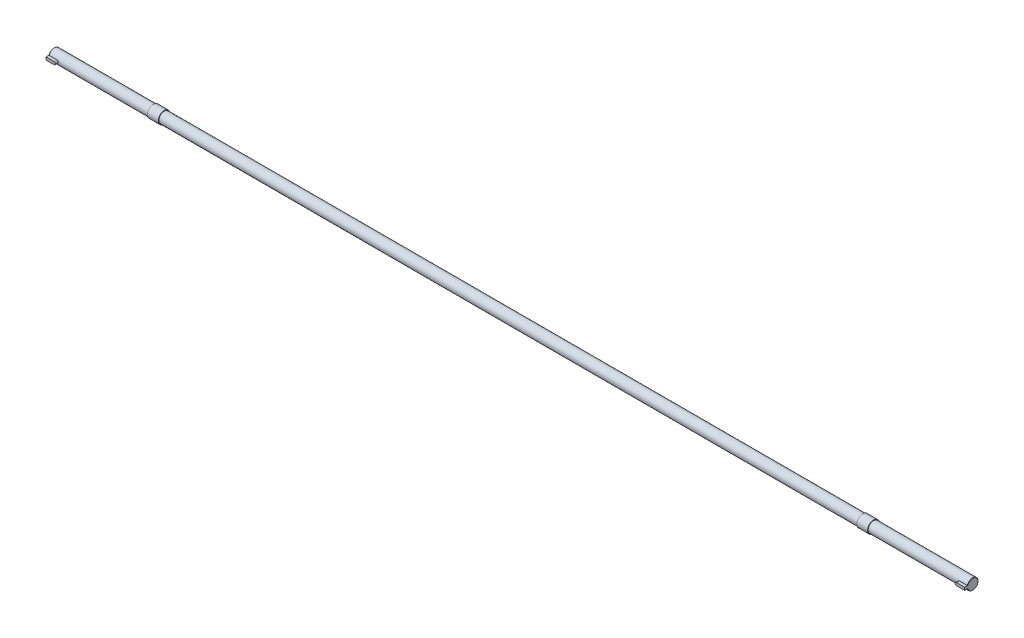
SolidWorks part; units mm, degrees
ref_plane "Front Plane" through (0, 0, 0) normal (0, 0, 1) x (1, 0, 0)
ref_plane "Top Plane" through (0, 0, 0) normal (0, 1, 0) x (1, 0, 0)
ref_plane "Right Plane" through (0, 0, 0) normal (1, 0, 0) x (0, 0, -1)
sketch "Sketch1" plane through (0, 0, 0) normal (0, 0, 1) x (1, 0, 0)
  line L0 (-1695, 0) -> (1695, 0)
  line L1 (1695, 0) -> (1695, -20)
  line L2 (1695, -20) -> (1328.75, -20)
  line L3 (1328.75, -20) -> (1328.75, -22)
  line L4 (1328.75, -22) -> (1288.75, -22)
  line L5 (1288.75, -22) -> (1288.75, -20)
  line L6 (1288.75, -20) -> (-1288.75, -20)
  line L7 (-1288.75, -20) -> (-1288.75, -22)
  line L8 (-1288.75, -22) -> (-1328.75, -22)
  line L9 (-1328.75, -22) -> (-1328.75, -20)
  line L10 (-1328.75, -20) -> (-1695, -20)
  line L11 (-1695, -20) -> (-1695, 0)
  point P3 (1308.75, -22)
  point P14 (-1308.75, -22)
  dimension "D3" = 20
  dimension "D4" = 22
  dimension "D5" = 22
  dimension "D6" = 40
  dimension "D7" = 40
  dimension "D8" = 3390
  dimension "D9" = 1695
  dimension "D10" = 386.25
  dimension "D11" = 386.25
revolve "Revolve1" add sketch "Sketch1" angle 360 about L0
chamfer "Chamfer1" distance 1 angle 45 2 edges at (-1695, -20, 0) (1695, -20, 0)
ref_plane "Plane1" through (0, 0, 20) normal (0, 0, 1) x (1, 0, 0)
sketch "Sketch3" plane through (0, 0, 20) normal (0, 0, 1) x (1, 0, 0)
  line L1 (1665, 5) -> (1695, 5)
  line L3 (1665, -5) -> (1695, -5)
  line L4 (1695, 5) -> (1695, -5)
  line L5 (1694, 20) -> (1328.75, 20) construction
  line L6 (0, 399.8509) -> (0, -460.5684) construction
  line L7 (-1695, 5) -> (-1695, -5)
  line L8 (-1665, -5) -> (-1695, -5)
  line L9 (-1665, 5) -> (-1695, 5)
  arc A0 (1665, 5) -> (1665, -5) centre (1665, 0) ccw
  arc A1 (-1665, 5) -> (-1665, -5) centre (-1665, 0) cw
  dimension "D3" = 10
  dimension "D1" = 10
  dimension "D2" = 30
  dimension "D4" = 15
extrude "Boss-Extrude2" add sketch "Sketch3" along normal blind 10 and the other way blind 5
